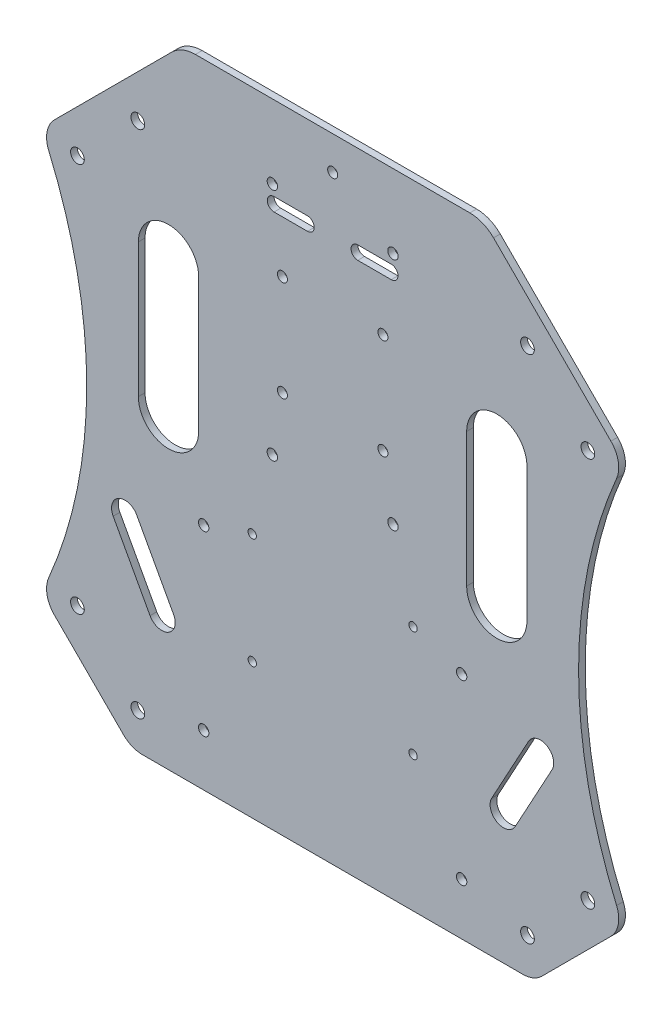
SolidWorks part; units mm, degrees
material "cf"
ref_plane "Front Plane" through (0, 0, 0) normal (0, 0, 1) x (1, 0, 0)
ref_plane "Top Plane" through (0, 0, 0) normal (0, 1, 0) x (1, 0, 0)
ref_plane "Right Plane" through (0, 0, 0) normal (1, 0, 0) x (0, 0, -1)
sketch "Sketch1" plane through (0, 0, 0) normal (0, 0, 1) x (1, 0, 0)
  line L0 (-82.7315, 60.1041) -> (-60.1041, 82.7315)
  line L5 (-27.5, -50) -> (27.5, -50) construction
  line L6 (-27.5, -50) -> (-27.5, -10) construction
  line L7 (-259.08, 259.08) -> (259.08, 259.08)
  line L8 (-259.08, 259.08) -> (-259.08, -259.08)
  line L9 (-259.08, -259.08) -> (259.08, -259.08)
  line L10 (259.08, 259.08) -> (259.08, -259.08)
  line L11 (-259.08, 259.08) -> (259.08, -259.08) construction
  line L12 (-259.08, -259.08) -> (259.08, 259.08) construction
  line L13 (-27.5, -10) -> (27.5, -10) construction
  line L14 (27.5, -50) -> (27.5, -10) construction
  line L15 (-27.5, -50) -> (27.5, -10) construction
  line L16 (-27.5, -10) -> (27.5, -50) construction
  line L17 (-17.5, 60) -> (17.5, 60) construction
  line L18 (-17.5, 60) -> (-17.5, 25) construction
  line L19 (-17.5, 25) -> (17.5, 25) construction
  line L20 (17.5, 60) -> (17.5, 25) construction
  line L21 (-76.1908, 58.1595) -> (-58.1595, 76.1908) construction
  line L23 (-82.7315, 60.1041) -> (-74.2462, 51.6188)
  line L24 (-60.1041, 82.7315) -> (-51.6188, 74.2462)
  line L25 (-74.2462, 51.6188) -> (-51.6188, 74.2462)
  line L26 (-82.7315, 60.1041) -> (-51.6188, 74.2462) construction
  line L27 (-60.1041, 82.7315) -> (-74.2462, 51.6188) construction
  line L28 (82.7315, -60.1041) -> (74.2462, -51.6188)
  line L29 (51.6188, -74.2462) -> (74.2462, -51.6188)
  line L30 (60.1041, -82.7315) -> (51.6188, -74.2462)
  line L31 (60.1041, -82.7315) -> (82.7315, -60.1041)
  line L32 (0, 0) -> (50000, 0) construction
  line L33 (60.1041, 82.7315) -> (82.7315, 60.1041)
  line L34 (60.1041, 82.7315) -> (51.6188, 74.2462)
  line L35 (51.6188, 74.2462) -> (74.2462, 51.6188)
  line L36 (82.7315, 60.1041) -> (74.2462, 51.6188)
  line L37 (-60.1041, -82.7315) -> (-51.6188, -74.2462)
  line L38 (-74.2462, -51.6188) -> (-51.6188, -74.2462)
  line L39 (-82.7315, -60.1041) -> (-74.2462, -51.6188)
  line L40 (-82.7315, -60.1041) -> (-60.1041, -82.7315)
  line L41 (-60.1041, 86.9741) -> (-47.3762, 74.2462)
  line L42 (-74.2462, 47.3762) -> (-47.3762, 74.2462)
  line L43 (-86.9741, 60.1041) -> (-74.2462, 47.3762)
  line L44 (-86.9741, 60.1041) -> (-60.1041, 86.9741)
  line L45 (60.1041, -86.9741) -> (86.9741, -60.1041)
  line L46 (60.1041, -86.9741) -> (47.3762, -74.2462)
  line L47 (47.3762, -74.2462) -> (74.2462, -47.3762)
  line L48 (86.9741, -60.1041) -> (74.2462, -47.3762)
  line L49 (60.1041, 86.9741) -> (47.3762, 74.2462)
  line L50 (47.3762, 74.2462) -> (74.2462, 47.3762)
  line L51 (86.9741, 60.1041) -> (74.2462, 47.3762)
  line L52 (60.1041, 86.9741) -> (86.9741, 60.1041)
  line L53 (-86.9741, -60.1041) -> (-60.1041, -86.9741)
  line L54 (-86.9741, -60.1041) -> (-74.2462, -47.3762)
  line L55 (-74.2462, -47.3762) -> (-47.3762, -74.2462)
  line L56 (-60.1041, -86.9741) -> (-47.3762, -74.2462)
  line L57 (0, 0) -> (0, 50000) construction
  line L58 (-60.1041, 86.9741) -> (60.1041, 86.9741)
  line L59 (-60.1041, -86.9741) -> (60.1041, -86.9741)
  line L61 (-30, -85) -> (30, -85)
  line L62 (-30, -85) -> (-30, 85)
  line L63 (-30, 85) -> (30, 85)
  line L64 (30, -85) -> (30, 85)
  line L65 (-30, -85) -> (30, 85) construction
  line L66 (-30, 85) -> (30, -85) construction
  line L67 (-55, -31.5) -> (55, -31.5) construction
  line L68 (-55, -31.5) -> (-55, 31.5) construction
  line L69 (-55, 31.5) -> (55, 31.5) construction
  line L70 (55, -31.5) -> (55, 31.5) construction
  line L71 (-55, -31.5) -> (55, 31.5) construction
  line L72 (-55, 31.5) -> (55, -31.5) construction
  arc A0 (-86.9741, -60.1041) -> (-86.9741, 60.1041) centre (-213.4158, 0) ccw
  arc A1 (86.9741, -60.1041) -> (86.9741, 60.1041) centre (213.4158, 0) cw
  circle A2 centre (-15, 57.5) radius 1.5
  circle A3 centre (-15, 27.5) radius 1.5
  circle A4 centre (15, 27.5) radius 1.5
  circle A5 centre (15, 57.5) radius 1.5
  circle A6 centre (-24, -13.5) radius 1.25
  circle A7 centre (24, -13.5) radius 1.25
  circle A8 centre (24, -46.5) radius 1.25
  circle A9 centre (-24, -46.5) radius 1.25
  circle A10 centre (-76.1908, 58.1595) radius 2.05
  circle A11 centre (-58.1595, 76.1908) radius 2.05
  circle A12 centre (76.1908, -58.1595) radius 2.05
  circle A13 centre (58.1595, -76.1908) radius 2.05
  circle A14 centre (-58.1595, -76.1908) radius 2.05
  circle A15 centre (-76.1908, -58.1595) radius 2.05
  circle A16 centre (58.1595, 76.1908) radius 2.05
  circle A17 centre (76.1908, 58.1595) radius 2.05
  circle A18 centre (-167.1561, -167.1561) radius 101.6 construction
  circle A19 centre (167.1561, 167.1561) radius 101.6 construction
  point P0 (0, 0)
  point P1 (0, -30)
  point P17 (-67.1751, 67.1751)
  point P48 (-60.8112, 60.8112)
  point P63 (0, 0)
  point P69 (0, 0)
  dimension "D12" = 140
  dimension "D18" = 3
  dimension "D24" = 2.5
  dimension "D36" = 4.1
  dimension "D42" = 203.2
  dimension "D43" = 472.7889
  dimension "D1" = 35
  dimension "D2" = 35
  dimension "D3" = 55
  dimension "D4" = 40
  dimension "D5" = 10
  dimension "D6" = 25
  dimension "D7" = 32
  dimension "D8" = 12
  dimension "D9" = 518.16
  dimension "D10" = 95
  dimension "D13" = 25.5
  dimension "D14" = 170
  dimension "D15" = 60
  dimension "D16" = 110
  dimension "D17" = 63
  dimension "D19" = 2.5
  dimension "D20" = 2.5
  dimension "D21" = 30
  dimension "D22" = 2.5
  dimension "D23" = 2.5
  dimension "D25" = 3.5
  dimension "D26" = 3.5
  dimension "D27" = 3.5
  dimension "D28" = 3.5
  dimension "D29" = 26.9741
  dimension "D35" = 12.75
  dimension "D37" = 280.3944
  dimension "D38" = 17.5
  dimension "D39" = 30
  dimension "D40" = 130
  dimension "D41" = 130
  dimension "D11" = 3
extrude "Boss-Extrude1" add sketch "Sketch1" along normal blind 2 contours L48 A1 L51 L50 L49 L58 L41 L42 L43 A0 L54 L55 L56 L59 L46 L47 L64 L61 L62 L63 | L53 L56 L55 L54 L40 L39 L38 L37 | L39 L40 L37 L38 | L30 L31 L28 L29 | L45 L48 L47 L46 L31 L30 L29 L28 | L52 L49 L50 L51 L33 L36 L35 L34 | L36 L33 L34 L35 | L44 L43 L42 L41 L25 L23 L0 L24 | L23 L25 L24 L0 | L61 L64 L63 L62
fillet "Fillet7" radius 8 8 edges at (86.9741, -60.1041, 1) (60.1041, -86.9741, 1) (-60.1041, -86.9741, 1) (-86.9741, -60.1041, 1) (-60.1041, 86.9741, 1) (60.1041, 86.9741, 1) (86.9741, 60.1041, 1) (-86.9741, 60.1041, 1)
sketch "Sketch2" plane through (0, 0, 2) normal (0, 0, 1) x (1, 0, 0)
  line L0 (-62.4472, 84.631) -> (-45.1041, 101.9741)
  line L1 (-45.1041, 101.9741) -> (45.1041, 101.9741)
  line L2 (0, 0) -> (0, 118.5934) construction
  line L3 (62.4472, 84.631) -> (45.1041, 101.9741)
  line L4 (62.4472, 84.631) -> (83.0638, 64.0144) construction
  line L5 (-56.7904, 86.9741) -> (56.7904, 86.9741) construction
  line L7 (-56.7904, 86.9741) -> (56.7904, 86.9741)
  arc A1 (62.4472, 84.631) -> (56.7904, 86.9741) centre (56.7904, 78.9741) ccw construction
  arc A2 (-56.7904, 86.9741) -> (-62.4472, 84.631) centre (-56.7904, 78.9741) ccw construction
  arc A3 (62.4472, 84.631) -> (56.7904, 86.9741) centre (56.7904, 78.9741) ccw
  arc A4 (-56.7904, 86.9741) -> (-62.4472, 84.631) centre (-56.7904, 78.9741) ccw
  dimension "D1" = 15
extrude "Boss-Extrude2" add sketch "Sketch2" against normal blind 2
fillet "Fillet8" radius 10 2 edges at (-45.1041, 101.9741, 1) (45.1041, 101.9741, 1)
sketch "Sketch4" plane through (0, 0, 2) normal (0, 0, 1) x (1, 0, 0)
  line L1 (-38.5, -71.5) -> (38.5, -71.5) construction
  line L2 (-38.5, -71.5) -> (-38.5, -18.5) construction
  line L3 (-38.5, -18.5) -> (38.5, -18.5) construction
  line L4 (38.5, -71.5) -> (38.5, -18.5) construction
  line L5 (-38.5, -71.5) -> (38.5, -18.5) construction
  line L6 (-38.5, -18.5) -> (38.5, -71.5) construction
  circle A0 centre (-38.5, -18.5) radius 1.55
  circle A1 centre (38.5, -18.5) radius 1.55
  circle A2 centre (38.5, -71.5) radius 1.55
  circle A3 centre (-38.5, -71.5) radius 1.55
  point P0 (0, -45)
  dimension "D4" = 3.1
  dimension "D1" = 77
  dimension "D2" = 53
  dimension "D3" = 45
extrude "Cut-Extrude1" cut sketch "Sketch4" against normal blind 2
sketch "Sketch5" plane through (0, 0, 2) normal (0, 0, 1) x (1, 0, 0)
  line L1 (-18, 80) -> (18, 80) construction
  line L2 (-18, 80) -> (-18, 10) construction
  line L3 (-18, 10) -> (18, 10) construction
  line L4 (18, 80) -> (18, 10) construction
  line L5 (-18, 80) -> (18, 10) construction
  line L6 (-18, 10) -> (18, 80) construction
  circle A0 centre (-18, 80) radius 1.55
  circle A1 centre (18, 80) radius 1.55
  circle A2 centre (18, 10) radius 1.55
  circle A3 centre (-18, 10) radius 1.55
  point P0 (0, 45)
  dimension "D3" = 3.1
  dimension "D1" = 70
  dimension "D2" = 36
  dimension "D4" = 45
extrude "Cut-Extrude2" cut sketch "Sketch5" against normal blind 2
sketch "Sketch6" plane through (0, 0, 2) normal (0, 0, 1) x (1, 0, 0)
  line L0 (-49, 45) -> (-49, 5) construction
  line L1 (-40, 45) -> (-40, 5)
  line L2 (-58, 45) -> (-58, 5)
  line L3 (0, 0) -> (0, 50000) construction
  line L4 (49, 45) -> (49, 5) construction
  line L5 (40, 45) -> (40, 5)
  line L6 (58, 45) -> (58, 5)
  line L7 (-62, -27.7751) -> (-51, -47.9741) construction
  line L8 (-58.4871, -25.8621) -> (-47.4871, -46.0611)
  line L9 (-65.5129, -29.6882) -> (-54.5129, -49.8872)
  line L10 (-56.7904, -86.9741) -> (56.7904, -86.9741) construction
  line L11 (62, -27.7751) -> (51, -47.9741) construction
  line L12 (58.4871, -25.8621) -> (47.4871, -46.0611)
  line L13 (65.5129, -29.6882) -> (54.5129, -49.8872)
  arc A0 (-40, 45) -> (-58, 45) centre (-49, 45) ccw
  arc A1 (-58, 5) -> (-40, 5) centre (-49, 5) ccw
  arc A2 (40, 45) -> (58, 45) centre (49, 45) cw
  arc A3 (58, 5) -> (40, 5) centre (49, 5) cw
  arc A4 (-58.4871, -25.8621) -> (-65.5129, -29.6882) centre (-62, -27.7751) ccw
  arc A5 (-54.5129, -49.8872) -> (-47.4871, -46.0611) centre (-51, -47.9741) ccw
  arc A6 (58.4871, -25.8621) -> (65.5129, -29.6882) centre (62, -27.7751) cw
  arc A7 (54.5129, -49.8872) -> (47.4871, -46.0611) centre (51, -47.9741) cw
  point P2 (-49, 25)
  point P12 (49, 25)
  point P19 (-56.5, -37.8746)
  point P28 (56.5, -37.8746)
  dimension "D2" = 9
  dimension "D8" = 62
  dimension "D1" = 40
  dimension "D3" = 49
  dimension "D4" = 5
  dimension "D5" = 23
  dimension "D6" = 8
  dimension "D7" = 51
  dimension "D9" = 39
extrude "Cut-Extrude3" cut sketch "Sketch6" against normal blind 10
sketch "Sketch7" plane through (0, 0, 2) normal (0, 0, 1) x (1, 0, 0)
  line L0 (40.9619, 101.9741) -> (-40.9619, 101.9741) construction
  line L1 (-17.5, 74.9741) -> (-7.5, 74.9741) construction
  line L2 (-17.5, 76.9741) -> (-7.5, 76.9741)
  line L3 (-17.5, 72.9741) -> (-7.5, 72.9741)
  line L4 (7.5, 74.9741) -> (17.5, 74.9741) construction
  line L5 (7.5, 76.9741) -> (17.5, 76.9741)
  line L6 (7.5, 72.9741) -> (17.5, 72.9741)
  line L7 (-12.5, 74.9741) -> (12.5, 74.9741) construction
  circle A0 centre (0, 91.9741) radius 1.5
  arc A1 (-17.5, 76.9741) -> (-17.5, 72.9741) centre (-17.5, 74.9741) ccw
  arc A2 (-7.5, 72.9741) -> (-7.5, 76.9741) centre (-7.5, 74.9741) ccw
  arc A3 (7.5, 76.9741) -> (7.5, 72.9741) centre (7.5, 74.9741) ccw
  arc A4 (17.5, 72.9741) -> (17.5, 76.9741) centre (17.5, 74.9741) ccw
  point P2 (-7.4939, 7.8651)
  point P4 (0, 33.7212)
  point P7 (-12.5, 74.9741)
  point P12 (12.5, 74.9741)
  point P21 (0, 74.9741)
  point P22 (7.5742, 2.8393)
  dimension "D2" = 3
  dimension "D7" = 2
  dimension "D1" = 10
  dimension "D3" = 10
  dimension "D4" = 25
  dimension "D5" = 27
  dimension "D6" = 10
extrude "Cut-Extrude4" cut sketch "Sketch7" against normal blind 10
